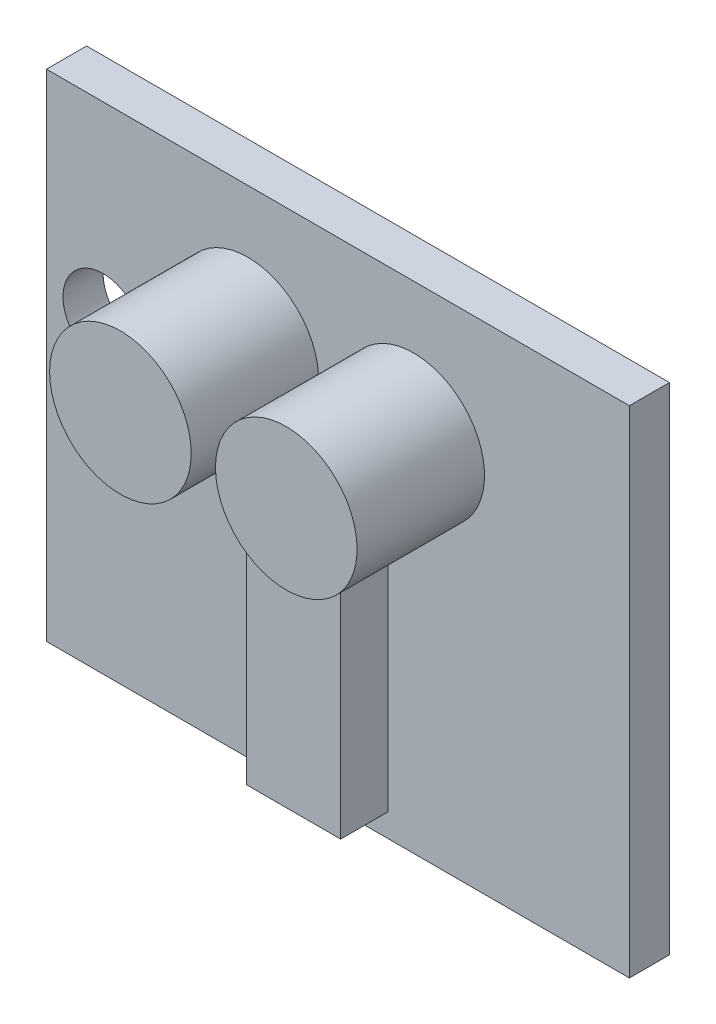
SolidWorks part; units mm, degrees
ref_plane "Спереди" through (0, 0, 0) normal (0, 0, 1) x (1, 0, 0)
ref_plane "Сверху" through (0, 0, 0) normal (0, 1, 0) x (1, 0, 0)
ref_plane "Справа" through (0, 0, 0) normal (1, 0, 0) x (0, 0, -1)
sketch "Эскиз1" plane through (0, 0, 0) normal (0, 0, 1) x (1, 0, 0)
  line L1 (-36.3576, 130.4948) -> (-11.6576, 130.4948)
  line L2 (-36.3576, 130.4948) -> (-36.3576, 109.4948)
  line L3 (-36.3576, 109.4948) -> (-11.6576, 109.4948)
  line L4 (-11.6576, 130.4948) -> (-11.6576, 109.4948)
  circle A0 centre (-33.9576, 122.4948) radius 1.7
  dimension "D3" = 3.4
  dimension "D1" = 21
  dimension "D2" = 24.7
  dimension "D4" = 2.4
  dimension "D5" = 8
extrude "Бобышка-Вытянуть1" add sketch "Эскиз1" along normal blind 1.7
sketch "Эскиз2" plane through (0, 0, 1.7) normal (0, 0, 1) x (1, 0, 0)
  circle A0 centre (-27.825, 124.8607) radius 3
  circle A1 centre (-20.7967, 124.8607) radius 3
  dimension "D1" = 6
extrude "Бобышка-Вытянуть2" add sketch "Эскиз2" along normal blind 5.4 contours A1
sketch "Эскиз3" plane through (0, 0, 1.7) normal (0, 0, 1) x (1, 0, 0)
  line L1 (-25.892, 110.474) -> (-21.892, 110.474)
  line L2 (-25.892, 110.474) -> (-25.892, 120.474)
  line L3 (-25.892, 120.474) -> (-21.892, 120.474)
  line L4 (-21.892, 110.474) -> (-21.892, 120.474)
  line L5 (-25.892, 110.474) -> (-21.892, 120.474) construction
  line L6 (-25.892, 120.474) -> (-21.892, 110.474) construction
  point P0 (-23.892, 115.474)
  dimension "D1" = 10
  dimension "D2" = 4
extrude "Бобышка-Вытянуть3" add sketch "Эскиз3" along normal blind 2
